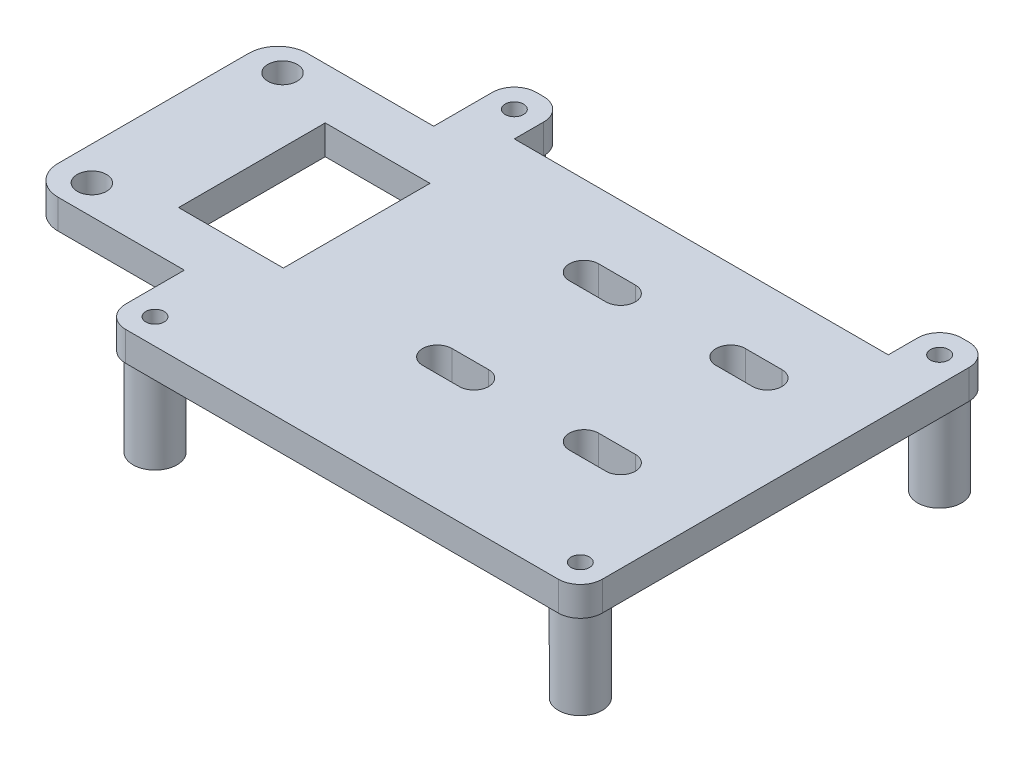
SolidWorks part; units mm, degrees
ref_plane "Front Plane" through (0, 0, 0) normal (0, 0, 1) x (1, 0, 0)
ref_plane "Top Plane" through (0, 0, 0) normal (0, 1, 0) x (1, 0, 0)
ref_plane "Right Plane" through (0, 0, 0) normal (1, 0, 0) x (0, 0, -1)
sketch "Sketch1" plane through (0, 0, 0) normal (0, 1, 0) x (1, 0, 0)
  line L0 (-29.1368, 21.2197) -> (-29.1368, 32.2197)
  line L1 (35.8632, -23.7803) -> (-29.1368, -23.7803)
  line L2 (35.8632, -23.7803) -> (35.8632, 32.2197)
  line L3 (35.8632, 32.2197) -> (28.8632, 32.2197)
  line L4 (-29.1368, -23.7803) -> (-29.1368, -12.7803)
  line L5 (-29.1368, 14.2197) -> (-22.6368, 14.2197)
  line L7 (-29.1368, -5.7803) -> (-22.6368, -5.7803)
  line L8 (-22.6368, 14.2197) -> (-22.6368, -5.7803)
  line L9 (-22.1368, 32.2197) -> (-29.1368, 32.2197)
  line L11 (-22.1368, 32.2197) -> (-22.1368, 25.2197)
  line L12 (-22.1368, 25.2197) -> (28.8632, 25.2197)
  line L13 (28.8632, 32.2197) -> (28.8632, 25.2197)
  line L16 (-11.6868, -12.7803) -> (-47.3584, -12.7803) construction
  line L18 (-47.3584, 21.2197) -> (-11.6868, 21.2197) construction
  line L19 (-46.3584, 21.2197) -> (-29.1368, 21.2197)
  line L20 (-29.1368, 14.2197) -> (-36.9231, 14.2197)
  line L22 (-29.1368, -5.7803) -> (-36.9231, -5.7803)
  line L23 (-36.9231, 14.2197) -> (-36.9231, -5.7803)
  line L27 (-50.3584, 17.2197) -> (-50.3584, -8.7803)
  line L28 (-46.3584, -12.7803) -> (-29.1368, -12.7803)
  circle A0 centre (32.3632, 28.7197) radius 1.25
  circle A1 centre (-25.6368, 28.7197) radius 1.25
  circle A2 centre (32.3632, -20.2803) radius 1.25
  circle A3 centre (-25.6368, -20.2803) radius 1.25
  circle A4 centre (-45.7494, 17.2197) radius 2
  circle A5 centre (-45.7494, -8.7803) radius 2
  arc A6 (-46.3584, 21.2197) -> (-50.3584, 17.2197) centre (-46.3584, 17.2197) ccw
  arc A7 (-50.3584, -8.7803) -> (-46.3584, -12.7803) centre (-46.3584, -8.7803) ccw
  point P0 (0, 0)
  point P14 (-29.1368, 4.2197)
  dimension "D11" = 2.5
  dimension "D12" = 2.5
  dimension "D13" = 2.5
  dimension "D14" = 2.5
  dimension "D22" = 4
  dimension "D2" = 56
  dimension "D3" = 3.5
  dimension "D4" = 3.5
  dimension "D5" = 3.5
  dimension "D6" = 3.5
  dimension "D7" = 3.5
  dimension "D8" = 3.5
  dimension "D9" = 3.5
  dimension "D10" = 3.5
  dimension "D15" = 3.5
  dimension "D16" = 20
  dimension "D17" = 7
  dimension "D18" = 3.5
  dimension "D19" = 58
  dimension "D20" = 18
  dimension "D21" = 7.7863
extrude "Boss-Extrude1" add sketch "Sketch1" along normal blind 4
fillet "Fillet1" radius 3 6 edges at (28.8632, 2, -32.2197) (35.8632, 2, -32.2197) (35.8632, 2, 23.7803) (-29.1368, 2, 23.7803) (-22.1368, 2, -32.2197) (-29.1368, 2, -32.2197)
sketch "Sketch2" plane through (0, 4, 0) normal (0, 1, 0) x (1, 0, 0)
  line L0 (-1.6368, 16.2197) -> (3.3632, 16.2197)
  line L2 (3.3632, 14.2197) -> (3.3632, -5.7803) construction
  line L3 (3.3632, -5.7803) -> (23.3632, -5.7803) construction
  line L4 (23.3632, 14.2197) -> (23.3632, -5.7803) construction
  line L6 (32.8632, 32.2197) -> (31.8632, 32.2197) construction
  line L7 (3.3632, 12.2197) -> (-1.6368, 12.2197)
  line L8 (-29.1368, -12.7803) -> (-29.1368, -20.7803) construction
  line L9 (18.3632, 16.2197) -> (23.3632, 16.2197)
  line L10 (23.3632, 12.2197) -> (18.3632, 12.2197)
  line L11 (23.3632, -3.7803) -> (18.3632, -3.7803)
  line L12 (23.3632, -7.7803) -> (18.3632, -7.7803)
  line L13 (-1.6368, -3.7803) -> (3.3632, -3.7803)
  line L14 (3.3632, -7.7803) -> (-1.6368, -7.7803)
  arc A0 (23.3632, 12.2197) -> (23.3632, 16.2197) centre (23.3632, 14.2197) ccw
  arc A1 (3.3632, 12.2197) -> (3.3632, 16.2197) centre (3.3632, 14.2197) ccw
  arc A2 (3.3632, -7.7803) -> (3.3632, -3.7803) centre (3.3632, -5.7803) ccw
  arc A3 (23.3632, -7.7803) -> (23.3632, -3.7803) centre (23.3632, -5.7803) ccw
  arc A4 (-1.6368, 16.2197) -> (-1.6368, 12.2197) centre (-1.6368, 14.2197) ccw
  arc A5 (-1.6368, -3.7803) -> (-1.6368, -7.7803) centre (-1.6368, -5.7803) ccw
  arc A6 (18.3632, 16.2197) -> (18.3632, 12.2197) centre (18.3632, 14.2197) ccw
  arc A7 (18.3632, -3.7803) -> (18.3632, -7.7803) centre (18.3632, -5.7803) ccw
  point P6 (3.3632, 4.2197)
  point P9 (32.3632, 32.2197)
  dimension "D5" = 5
  dimension "D7" = 5
  dimension "D1" = 32.5
  dimension "D2" = 28
  dimension "D3" = 20
  dimension "D4" = 20
  dimension "D6" = 5
  dimension "D8" = 5
extrude "Cut-Extrude1" cut sketch "Sketch2" against normal blind 4
sketch "Sketch3" plane through (0, 0, 0) normal (0, -1, 0) x (1, 0, 0)
  circle A0 centre (-25.6368, 20.2803) radius 3
  circle A2 centre (-25.6368, -28.7197) radius 3
  circle A3 centre (32.3632, -28.7197) radius 3
  circle A4 centre (32.3632, 20.2803) radius 3
  circle A5 centre (-25.6368, 20.2803) radius 1.25
  circle A6 centre (32.3632, 20.2803) radius 1.25
  circle A8 centre (32.3632, -28.7197) radius 1.25
  circle A9 centre (-25.6368, -28.7197) radius 1.25
extrude "Boss-Extrude2" add sketch "Sketch3" along normal blind 12
